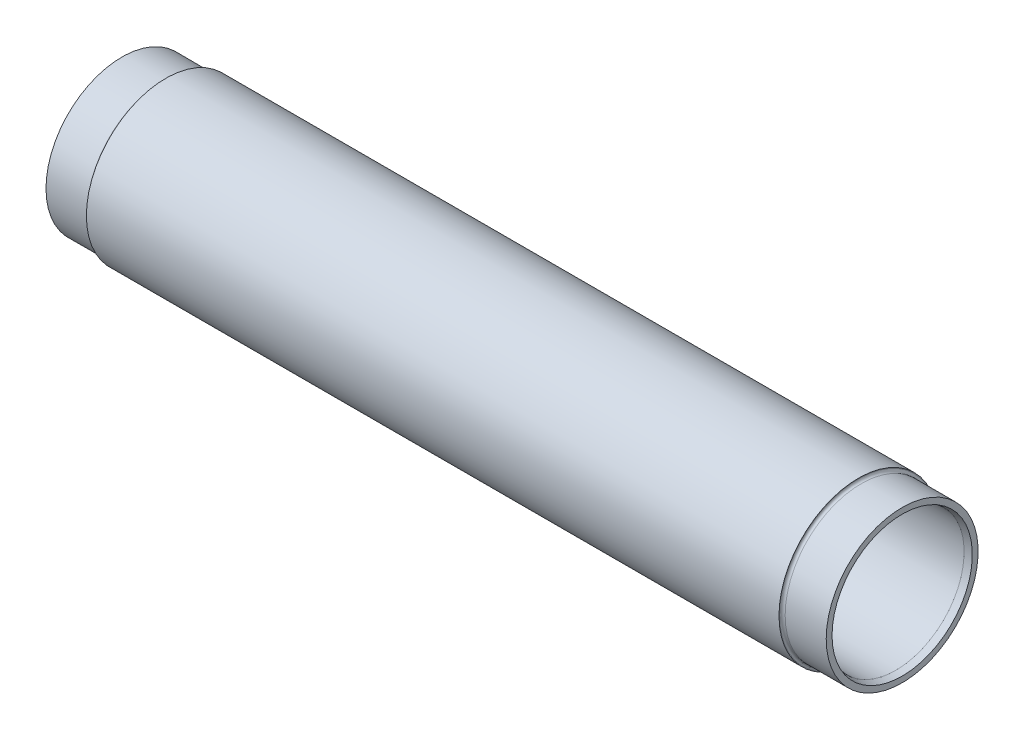
SolidWorks part; units mm, degrees
ref_plane "Front Plane" through (0, 0, 0) normal (0, 0, 1) x (1, 0, 0)
ref_plane "Top Plane" through (0, 0, 0) normal (0, 1, 0) x (1, 0, 0)
ref_plane "Right Plane" through (0, 0, 0) normal (1, 0, 0) x (0, 0, -1)
sketch "Sketch1" plane through (0, 0, 0) normal (0, 1, 0) x (1, 0, 0)
  line L0 (0, 0) -> (0, 50) construction
  line L1 (0, 51.25) -> (0, 55.5)
  line L2 (0, 55.5) -> (32, 55.5)
  line L3 (32, 55.5) -> (32, 58)
  line L4 (32, 58) -> (538, 58)
  line L5 (538, 58) -> (538, 55.5)
  line L6 (538, 55.5) -> (570, 55.5)
  line L7 (570, 55.5) -> (570, 51.25)
  line L8 (565.25, 50) -> (4.75, 50)
  line L9 (4.75, 50) -> (0, 51.25)
  line L10 (570, 51.25) -> (565.25, 50)
  line L11 (0, 0) -> (39.0282, 0) construction
  point P10 (570, 50)
  dimension "D1" = 50
  dimension "D2" = 570
  dimension "D3" = 5.5
  dimension "D4" = 8
  dimension "D5" = 32
  dimension "D6" = 4.75
  dimension "D7" = 1.25
  dimension "D8" = 32
  dimension "D9" = 5.5
  dimension "D10" = 1.25
  dimension "D11" = 4.75
revolve "Revolve1" add sketch "Sketch1" angle 360 about L11
fillet "Fillet1" radius 2 2 edges at (538, 0, 55.5) (32, 0, 55.5)
